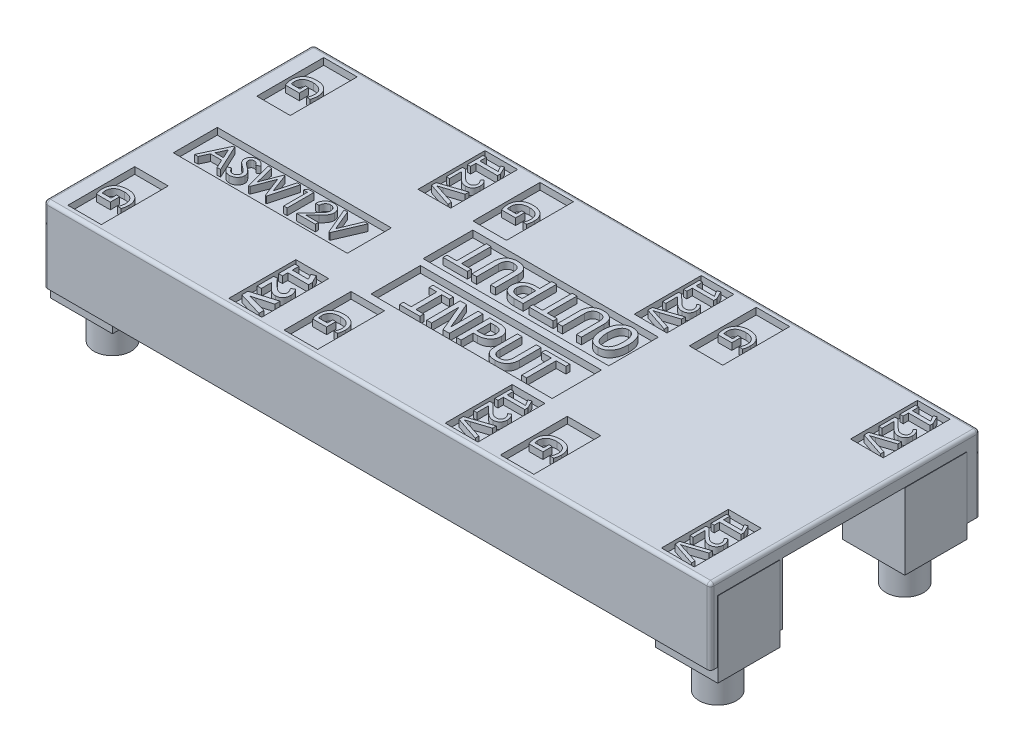
SolidWorks part; units mm, degrees
ref_plane "Front Plane" through (0, 0, 0) normal (0, 0, 1) x (1, 0, 0)
ref_plane "Top Plane" through (0, 0, 0) normal (0, 1, 0) x (1, 0, 0)
ref_plane "Right Plane" through (0, 0, 0) normal (1, 0, 0) x (0, 0, -1)
sketch "Sketch1" plane through (0, 16.7986, 0) normal (0, 1, 0) x (1, 0, 0)
  line L1 (-67.5438, 21.3648) -> (32.0242, 21.3648)
  line L2 (-67.5438, 21.3648) -> (-67.5438, -18.8942)
  line L3 (-67.5438, -18.8942) -> (32.0242, -18.8942)
  line L4 (32.0242, 21.3648) -> (32.0242, -18.8942)
  line L6 (-32.7768, 21.8648) -> (-1.7768, 21.8648) construction
  line L7 (29.2472, -19.3942) -> (-0.7528, -19.3942) construction
  line L10 (32.0242, -28.4742) -> (32.0242, -18.1697) construction
  line L11 (-67.5438, 35.0258) -> (-67.5438, 19.6413) construction
  dimension "D1" = 0.5
  dimension "D2" = 0.5
  dimension "D3" = 0
extrude "main volume boss" add sketch "Sketch1" against normal up to surface (11.2986 mm away) from offset 3.5
sketch "Sketch3" plane through (0, 20.2986, 0) normal (0, -1, 0) x (1, 0, 0)
  line L1 (32.0242, -19.3648) -> (-66.0438, -19.3648)
  line L2 (32.0242, -19.3648) -> (32.0242, 16.8942)
  line L3 (32.0242, 16.8942) -> (-66.0438, 16.8942)
  line L4 (-66.0438, -19.3648) -> (-66.0438, 16.8942)
  line L5 (-67.5438, 18.8942) -> (32.0242, 18.8942) construction
  line L6 (32.0242, -21.3648) -> (-67.5438, -21.3648) construction
  line L7 (32.0242, 18.8942) -> (32.0242, -21.3648) construction
  line L8 (-67.5438, -21.3648) -> (-67.5438, 18.8942) construction
  dimension "D1" = 1.5
  dimension "D2" = 2
  dimension "D3" = 2
  dimension "D4" = 0
extrude "hollow out main" cut sketch "Sketch3" against normal up to surface (9.2986 mm away) from offset 2
sketch "Sketch4" plane through (0, 18.2986, 0) normal (0, -1, 0) x (1, 0, 0)
  circle A0 centre (-62.9718, 13.2342) radius 2.794
  circle A1 centre (-62.9718, -14.7058) radius 2.794
  circle A2 centre (27.4522, 13.2342) radius 2.794
  circle A3 centre (27.4522, -14.7058) radius 2.794
extrude "screw pillars" add sketch "Sketch4" along normal up to surface (16.8 mm away)
sketch "Sketch5" plane through (32.0242, 0, 0) normal (1, 0, 0) x (0, 0, -1)
  line L0 (-7.9002, 16.7986) -> (-7.9002, 1.4986) construction
  line L1 (-18.8942, 20.2986) -> (-8.1002, 20.2986)
  line L2 (-18.8942, 20.2986) -> (-18.8942, 9.1)
  line L3 (-18.8942, 9.1) -> (-8.1002, 9.1)
  line L4 (-8.1002, 20.2986) -> (-8.1002, 9.1)
  line L5 (21.3648, 20.2986) -> (10.0798, 20.2986)
  line L6 (21.3648, 20.2986) -> (21.3648, 9.1)
  line L7 (21.3648, 9.1) -> (10.0798, 9.1)
  line L8 (10.0798, 20.2986) -> (10.0798, 9.1)
  line L9 (9.8798, 16.7986) -> (9.8798, 1.4986) construction
  line L10 (-28.4742, 9) -> (-18.1697, 9) construction
  dimension "D1" = 0.2
  dimension "D2" = 0.2
  dimension "D3" = 0.1
  dimension "D4" = 0.1
extrude "USB side vertical boss" add sketch "Sketch5" against normal blind 1.5
sketch "Sketch6" plane through (0, 18.2986, 0) normal (0, -1, 0) x (1, 0, 0)
  line L1 (-67.6073, 8.5987) -> (-58.3363, 8.5987)
  line L2 (-67.6073, 8.5987) -> (-67.6073, 17.8697)
  line L3 (-67.6073, 17.8697) -> (-58.3363, 17.8697)
  line L4 (-58.3363, 8.5987) -> (-58.3363, 17.8697)
  line L5 (-67.6073, 8.5987) -> (-58.3363, 17.8697) construction
  line L6 (-67.6073, 17.8697) -> (-58.3363, 8.5987) construction
  line L7 (-67.6073, -19.3413) -> (-58.3363, -19.3413)
  line L8 (-67.6073, -19.3413) -> (-67.6073, -10.0703)
  line L9 (-67.6073, -10.0703) -> (-58.3363, -10.0703)
  line L10 (-58.3363, -19.3413) -> (-58.3363, -10.0703)
  line L11 (-67.6073, -19.3413) -> (-58.3363, -10.0703) construction
  line L12 (-67.6073, -10.0703) -> (-58.3363, -19.3413) construction
  line L13 (32.0877, 17.8697) -> (22.8167, 17.8697)
  line L14 (32.0877, 17.8697) -> (32.0877, 8.5987)
  line L15 (32.0877, 8.5987) -> (22.8167, 8.5987)
  line L16 (22.8167, 17.8697) -> (22.8167, 8.5987)
  line L17 (32.0877, 17.8697) -> (22.8167, 8.5987) construction
  line L18 (32.0877, 8.5987) -> (22.8167, 17.8697) construction
  line L19 (32.0877, -19.3413) -> (22.8167, -19.3413)
  line L20 (32.0877, -19.3413) -> (32.0877, -10.0703)
  line L21 (32.0877, -10.0703) -> (22.8167, -10.0703)
  line L22 (22.8167, -19.3413) -> (22.8167, -10.0703)
  line L23 (32.0877, -19.3413) -> (22.8167, -10.0703) construction
  line L24 (32.0877, -10.0703) -> (22.8167, -19.3413) construction
  point P0 (-62.9718, 13.2342)
  point P6 (-62.9718, -14.7058)
  point P12 (27.4522, 13.2342)
  point P18 (27.4522, -14.7058)
  dimension "D1" = 9.271
extrude "boss for screws" add sketch "Sketch6" along normal offset from surface (11.3 mm away) 5.5 up to face at (27.4522, 1.4986, -11.9118)
sketch "Sketch7" plane through (0, 1.4986, 0) normal (0, -1, 0) x (1, 0, 0)
  circle A0 centre (27.4522, 13.2342) radius 1.524
  circle A1 centre (27.4522, -14.7058) radius 1.524
  circle A2 centre (-62.9718, -14.7058) radius 1.524
  circle A3 centre (-62.9718, 13.2342) radius 1.524
extrude "screw holes" cut sketch "Sketch7" against normal blind 15.24
fillet "Fillet1" radius 0.5 8 edges at (-17.7598, 20.2986, 18.8942) (-67.5438, 20.2986, -1.2353) (-17.7598, 20.2986, -21.3648) (32.0242, 20.2986, -1.2353) (-67.5438, 14.6493, 18.8942) (-67.5438, 14.6493, -21.3648) (32.0242, 14.6493, -21.3648) (32.0242, 14.6493, 18.8942)
sketch "Sketch8" plane through (22.8167, 0, 0) normal (-1, 0, 0) x (0, 0, 1)
  line L0 (10.4402, 6.9986) -> (16.0282, 6.9986) construction
  line L5 (9.9322, 12.3006) -> (16.5362, 12.3006)
  line L6 (9.9322, 12.3006) -> (9.9322, 8.9986)
  line L7 (9.9322, 8.9986) -> (16.5362, 8.9986)
  line L8 (16.5362, 12.3006) -> (16.5362, 8.9986)
  line L9 (8.5987, 6.9986) -> (17.8697, 6.9986) construction
  line L11 (-11.4038, 8.9986) -> (-18.0078, 8.9986)
  line L12 (-11.4038, 8.9986) -> (-11.4038, 12.3006)
  line L13 (-11.4038, 12.3006) -> (-18.0078, 12.3006)
  line L14 (-18.0078, 8.9986) -> (-18.0078, 12.3006)
  line L15 (-19.3413, 6.9986) -> (-10.0703, 6.9986) construction
  point P6 (13.2342, 6.9986)
  point P7 (13.2342, 8.9986)
  point P14 (-14.7058, 8.9986)
  point P19 (-14.7058, 6.9986)
  dimension "D1" = 6.604
  dimension "D2" = 3.302
  dimension "D3" = 2
extrude "nut holder cutout right" cut sketch "Sketch8" against normal blind 8.636
sketch "Sketch9" plane through (-58.3363, 0, 0) normal (1, 0, 0) x (0, 0, -1)
  line L0 (18.0078, 12.3006) -> (18.0078, 8.9986) construction
  line L1 (18.0078, 12.3006) -> (11.4038, 12.3006)
  line L2 (18.0078, 12.3006) -> (18.0078, 8.9986)
  line L3 (18.0078, 8.9986) -> (11.4038, 8.9986)
  line L4 (11.4038, 12.3006) -> (11.4038, 8.9986)
  line L5 (11.4038, 12.3006) -> (18.0078, 12.3006) construction
  line L6 (-9.9322, 12.3006) -> (-9.9322, 8.9986) construction
  line L7 (-9.9322, 8.9986) -> (-16.5362, 8.9986)
  line L8 (-9.9322, 8.9986) -> (-9.9322, 12.3006)
  line L9 (-9.9322, 12.3006) -> (-16.5362, 12.3006)
  line L10 (-16.5362, 8.9986) -> (-16.5362, 12.3006)
  line L11 (-9.9322, 8.9986) -> (-16.5362, 8.9986) construction
extrude "nut holder cutout left" cut sketch "Sketch9" against normal blind 8.636
sketch "Sketch12" plane through (0, 20.2986, 0) normal (0, 1, 0) x (1, 0, 0)
  line L0 (-67.5438, -18.3942) -> (-67.5438, 20.8648) construction
  line L1 (-31.5526, 9.1728) -> (-3.8272, 9.1728)
  line L2 (-31.5526, 9.1728) -> (-31.5526, 1.7569)
  line L3 (-31.5526, 1.7569) -> (-3.8272, 1.7569)
  line L4 (-3.8272, 9.1728) -> (-3.8272, 1.7569)
  line L5 (-63.9129, 3.3605) -> (-37.9129, 3.3605)
  line L6 (-63.9129, 3.3605) -> (-63.9129, -3.2127)
  line L7 (-63.9129, -3.2127) -> (-37.9129, -3.2127)
  line L8 (-37.9129, 3.3605) -> (-37.9129, -3.2127)
  line L9 (-30.8784, 0.6638) -> (-3.8272, 0.6638)
  line L10 (-30.8784, 0.6638) -> (-30.8784, -6.7022)
  line L11 (-30.8784, -6.7022) -> (-3.8272, -6.7022)
  line L12 (-3.8272, 0.6638) -> (-3.8272, -6.7022)
  line L13 (31.5242, -18.8942) -> (-67.0438, -18.8942) construction
  line L14 (-67.0438, 21.3648) -> (31.5242, 21.3648) construction
  line L15 (-32.695, 20.3488) -> (-32.695, 10.3488)
  line L16 (-65.0038, -7.8782) -> (-60.0038, -7.8782)
  line L17 (-65.0038, -7.8782) -> (-65.0038, -17.8782)
  line L18 (-65.0038, -17.8782) -> (-60.0038, -17.8782)
  line L19 (-60.0038, -7.8782) -> (-60.0038, -17.8782)
  line L20 (-40.9369, -7.8782) -> (-36.0368, -7.8782)
  line L21 (-40.9369, -7.8782) -> (-40.9369, -17.8782)
  line L22 (-40.9369, -17.8782) -> (-36.0368, -17.8782)
  line L23 (-36.0368, -7.8782) -> (-36.0368, -17.8782)
  line L24 (-65.0038, 20.3488) -> (-60.0038, 20.3488)
  line L25 (-65.0038, 20.3488) -> (-65.0038, 10.3488)
  line L26 (-65.0038, 10.3488) -> (-60.0038, 10.3488)
  line L27 (-60.0038, 20.3488) -> (-60.0038, 10.3488)
  line L28 (-40.9129, 20.3488) -> (-36.0368, 20.3488)
  line L29 (-40.9129, 20.3488) -> (-40.9129, 10.3488)
  line L30 (-40.9129, 10.3488) -> (-36.0368, 10.3488)
  line L31 (-36.0368, 20.3488) -> (-36.0368, 10.3488)
  line L32 (-27.695, 20.3488) -> (-27.695, 10.3488)
  line L33 (-8.6041, 20.3488) -> (-8.6041, 10.3488)
  line L34 (-3.728, 20.3488) -> (-3.728, 10.3488)
  line L35 (-32.695, -7.8782) -> (-32.695, -17.8782)
  line L36 (-27.695, -7.8782) -> (-27.695, -17.8782)
  line L37 (-8.6281, -7.8782) -> (-8.6281, -17.8782)
  line L38 (-3.728, -7.8782) -> (-3.728, -17.8782)
  line L39 (-8.6281, -17.8782) -> (-3.728, -17.8782)
  line L40 (-8.6281, -7.8782) -> (-3.728, -7.8782)
  line L41 (-8.6041, 10.3488) -> (-3.728, 10.3488)
  line L42 (-8.6041, 20.3488) -> (-3.728, 20.3488)
  line L43 (-32.695, 20.3488) -> (-27.695, 20.3488)
  line L44 (-32.695, 10.3488) -> (-27.695, 10.3488)
  line L45 (-32.695, -7.8782) -> (-27.695, -7.8782)
  line L46 (-32.695, -17.8782) -> (-27.695, -17.8782)
  line L47 (-0.3862, 20.3488) -> (-0.3862, 10.3488)
  line L48 (4.6138, 20.3488) -> (4.6138, 10.3488)
  line L49 (23.7047, 20.3488) -> (23.7047, 10.3488)
  line L50 (28.5808, 20.3488) -> (28.5808, 10.3488)
  line L51 (-0.3862, -7.8782) -> (-0.3862, -17.8782)
  line L52 (4.6138, -7.8782) -> (4.6138, -17.8782)
  line L53 (23.6807, -7.8782) -> (23.6807, -17.8782)
  line L54 (28.5808, -7.8782) -> (28.5808, -17.8782)
  line L55 (23.6807, -17.8782) -> (28.5808, -17.8782)
  line L56 (23.6807, -7.8782) -> (28.5808, -7.8782)
  line L57 (23.7047, 10.3488) -> (28.5808, 10.3488)
  line L58 (23.7047, 20.3488) -> (28.5808, 20.3488)
  line L59 (-0.3862, 20.3488) -> (4.6138, 20.3488)
  line L60 (-0.3862, 10.3488) -> (4.6138, 10.3488)
  line L61 (-0.3862, -7.8782) -> (4.6138, -7.8782)
  line L62 (-0.3862, -17.8782) -> (4.6138, -17.8782)
  dimension "D1" = 26
  dimension "D2" = 7.4159
  dimension "D3" = 27.7254
  dimension "D4" = 27.0512
  dimension "D5" = 7.366
  dimension "D6" = 6.5732
  dimension "D7" = 12.192
  dimension "D8" = 12.192
  dimension "D9" = 10
  dimension "D10" = 5
  dimension "D11" = 2.54
  dimension "D12" = 1.016
  dimension "D13" = 1.016
  dimension "D14" = 24.0669
  dimension "D15" = 3
extrude "lettering cutout" cut sketch "Sketch12" against normal blind 1
sketch "Sketch10" plane through (0, 19.2986, 0) normal (0, 1, 0) x (1, 0, 0)
  line L0 (-31.5526, 1.7569) -> (-3.8272, 1.7569) construction
  line L1 (-30.8784, -6.7022) -> (-3.8272, -6.7022) construction
  line L2 (-63.9129, -3.2127) -> (-37.9129, -3.2127) construction
  line L3 (-64.4958, 20.3488) -> (-64.4958, 10.3488) construction
  line L4 (-60.0038, 20.3488) -> (-65.0038, 20.3488) construction
  line L5 (-65.0038, 10.3488) -> (-60.0038, 10.3488) construction
  line L6 (-40.4289, -7.8782) -> (-40.4289, -17.8782) construction
  line L7 (-36.0368, -7.8782) -> (-40.9369, -7.8782) construction
  line L8 (-40.9369, -17.8782) -> (-36.0368, -17.8782) construction
  line L9 (-3.8272, 8.4108) -> (-31.5526, 8.4108) construction
  line L10 (-65.0038, 20.3488) -> (-65.0038, 10.3488) construction
  line L11 (-40.9369, -7.8782) -> (-40.9369, -17.8782) construction
  line L12 (-3.8272, 1.7569) -> (-3.8272, 9.1728) construction
  line L13 (-31.5526, 9.1728) -> (-31.5526, 1.7569) construction
  line L14 (-3.8272, 9.1728) -> (-31.5526, 9.1728) construction
  line L15 (-30.8784, -5.9402) -> (-3.8272, -5.9402) construction
  line L16 (-30.8784, 0.6638) -> (-30.8784, -6.7022) construction
  line L17 (-3.8272, -6.7022) -> (-3.8272, 0.6638) construction
  line L18 (-64.4958, -7.8782) -> (-64.4958, -17.8782) construction
  line L19 (-60.0038, -7.8782) -> (-65.0038, -7.8782) construction
  line L20 (-65.0038, -17.8782) -> (-60.0038, -17.8782) construction
  line L26 (-40.4289, 20.3488) -> (-40.4289, 10.3488) construction
  line L27 (-40.9129, 10.3488) -> (-36.0368, 10.3488) construction
  line L28 (-8.1201, 20.3488) -> (-8.1201, 10.3488) construction
  line L29 (-32.187, 20.3488) -> (-32.187, 10.3488) construction
  line L30 (-32.187, -7.8782) -> (-32.187, -17.8782) construction
  line L31 (-8.1201, -7.8782) -> (-8.1201, -17.8782) construction
  line L32 (24.1887, 20.3488) -> (24.1887, 10.3488) construction
  line L33 (0.1218, 20.3488) -> (0.1218, 10.3488) construction
  line L34 (0.1218, -7.8782) -> (0.1218, -17.8782) construction
  line L35 (24.1887, -7.8782) -> (24.1887, -17.8782) construction
  text T0 "INPUT" font "Consolas" height 5
  text T1 "OUTPUT" font "Consolas" height 5
  text T2 "<b>ASW12V</b>" font "Century Gothic" height 4
  text T3 "G" font "Consolas" height 4
  text T4 "<b>12V</b>" font "Consolas" height 3.683
  text T5 "G" font "Consolas" height 4
  text T6 "12V" font "Consolas" height 3.683
  text T7 "12V" font "Consolas" height 3.683
  text T8 "12V" font "Consolas" height 3.683
  text T9 "12V" font "Consolas" height 3.683
  text T10 "12V" font "Consolas" height 3.683
  text T11 "G" font "Consolas" height 4
  text T12 "G" font "Consolas" height 4
  text T13 "G" font "Consolas" height 4
  text T14 "G" font "Consolas" height 4
  dimension "D1" = 1.3529
  dimension "D2" = 1.515
  dimension "D3" = 1.3739
  dimension "D4" = 0.508
  dimension "D5" = 0.508
  dimension "D6" = 0.762
  dimension "D7" = 0.762
  dimension "D8" = 3
extrude "lettering" add sketch "Sketch10" along normal blind 1
